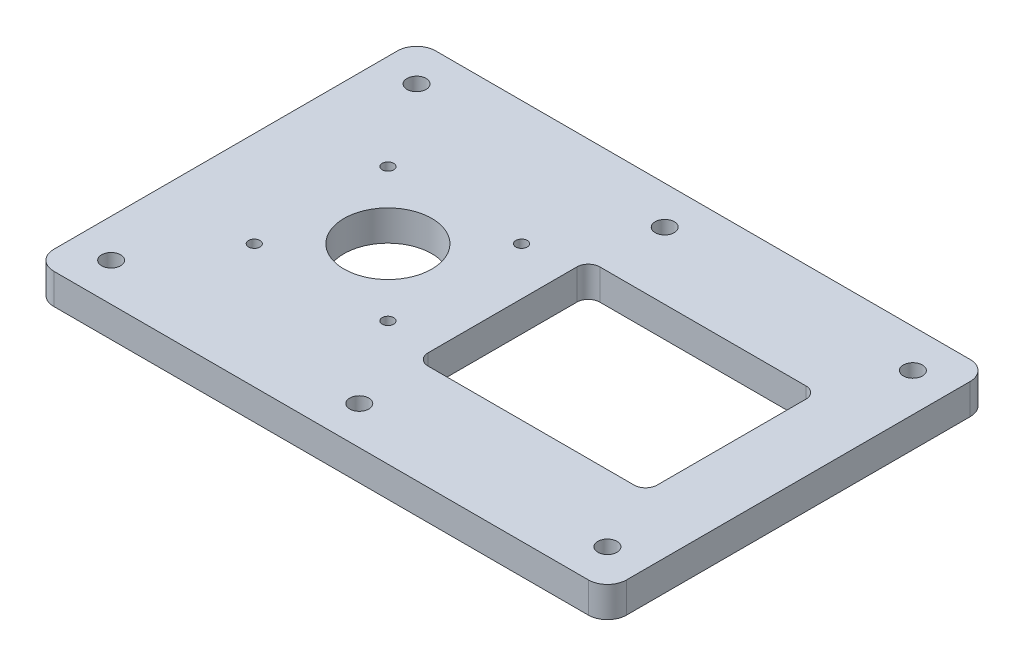
SolidWorks part; units mm, degrees
material "Pine"
ref_plane "Front Plane" through (0, 0, 0) normal (0, 0, 1) x (1, 0, 0)
ref_plane "Top Plane" through (0, 0, 0) normal (0, 1, 0) x (1, 0, 0)
ref_plane "Right Plane" through (0, 0, 0) normal (1, 0, 0) x (0, 0, -1)
sketch "Sketch1" plane through (0, 0, 0) normal (0, 1, 0) x (1, 0, 0)
  line L0 (27.5, 0) -> (27.5, 22.5)
  line L1 (-75, -50) -> (75, -50)
  line L2 (-75, -50) -> (-75, 50)
  line L3 (-75, 50) -> (75, 50)
  line L4 (75, -50) -> (75, 50)
  line L5 (-75, -50) -> (75, 50) construction
  line L6 (-75, 50) -> (75, -50) construction
  line L7 (-65, -40) -> (65, -40)
  line L8 (-65, -40) -> (-65, 40)
  line L9 (-65, 40) -> (65, 40)
  line L10 (65, -40) -> (65, 40)
  line L11 (-65, -40) -> (65, 40) construction
  line L12 (-65, 40) -> (65, -40) construction
  line L13 (-32.5, 0) -> (27.5, 0)
  line L14 (-50, -17.5) -> (-15, -17.5)
  line L15 (-50, -17.5) -> (-50, 17.5)
  line L16 (-50, 17.5) -> (-15, 17.5)
  line L17 (-15, -17.5) -> (-15, 17.5)
  line L18 (-50, -17.5) -> (-15, 17.5) construction
  line L19 (-50, 17.5) -> (-15, -17.5) construction
  line L20 (27.5, 22.5) -> (50, 22.5)
  line L24 (50, 22.5) -> (57.5, 22.5)
  line L25 (57.5, 22.5) -> (-2.5, 22.5)
  line L32 (-2.5, 22.5) -> (57.5, 22.5)
  line L33 (-2.5, 22.5) -> (-2.5, -22.5)
  line L38 (-2.5, -22.5) -> (57.5, -22.5)
  line L41 (27.5, 0) -> (35.5, 0)
  line L42 (57.5, 22.5) -> (57.5, -22.5)
  circle A0 centre (-65, 40) radius 2.5
  circle A1 centre (0, 40) radius 2.5
  circle A2 centre (65, 40) radius 2.5
  circle A3 centre (0, -40) radius 2.5
  circle A4 centre (65, -40) radius 2.5
  circle A5 centre (-65, -40) radius 2.5
  circle A6 centre (-32.5, 0) radius 11.5
  circle A7 centre (-50, 17.5) radius 1.5
  circle A25 centre (-15, 17.5) radius 1.5
  circle A26 centre (-15, -17.5) radius 1.5
  circle A27 centre (-50, -17.5) radius 1.5
  point P0 (0, 0)
  point P5 (0, 0)
  dimension "D5" = 3
  dimension "D7" = 5
  dimension "D8" = 23
  dimension "D11" = 3
  dimension "D13" = 3
  dimension "D17" = 45
  dimension "D1" = 150
  dimension "D2" = 100
  dimension "D3" = 10
  dimension "D4" = 10
  dimension "D9" = 32.5
  dimension "D10" = 35
  dimension "D14" = 22.5
  dimension "D15" = 60
  dimension "D16" = 60
  dimension "D12" = 22.5
  dimension "D6" = 2
extrude "Boss-Extrude1" add sketch "Sketch1" along normal blind 8
fillet "Fillet2" radius 5 4 edges at (-75, 4, -50) (75, 4, -50) (75, 4, 50) (-75, 4, 50)
fillet "Fillet4" radius 3 4 edges at (57.5, 4, 22.5) (57.5, 4, -22.5) (-2.5, 4, 22.5) (-2.5, 4, -22.5)
